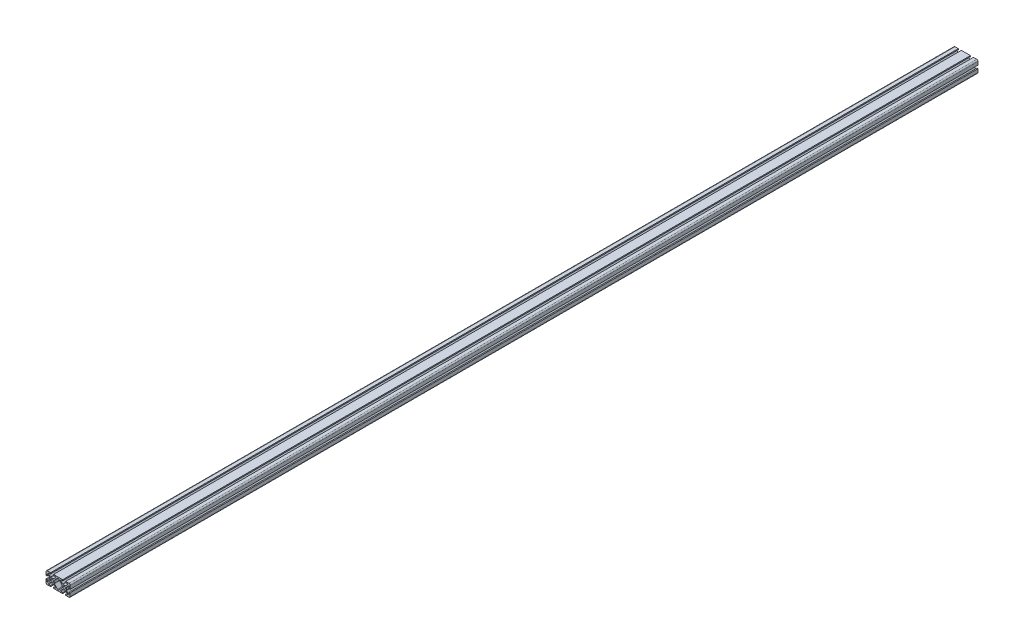
SolidWorks part; units mm, degrees
ref_plane "Front Plane" through (0, 0, 0) normal (0, 0, 1) x (1, 0, 0)
ref_plane "Top Plane" through (0, 0, 0) normal (0, 1, 0) x (1, 0, 0)
ref_plane "Right Plane" through (0, 0, 0) normal (1, 0, 0) x (0, 0, -1)
sketch "Sketch1" plane through (0, 0, 0) normal (0, 0, 1) x (1, 0, 0)
  line L0 (10, 10) -> (10, -10) construction
  line L1 (-20, 0) -> (20, 0) construction
  line L2 (12.5, -10) -> (20, -10)
  line L3 (20, -10) -> (20, -2.5)
  line L4 (12.5, -10) -> (12.5, -8.2134)
  line L5 (12.5, -8.2134) -> (16.95, -8.2134)
  line L6 (16.95, -8.2134) -> (12.3366, -3.6)
  line L7 (10, 0) -> (20, -10) construction
  line L8 (20, -2.5) -> (18.2134, -2.5)
  line L9 (18.2134, -2.5) -> (18.2134, -6.95)
  line L10 (18.2134, -6.95) -> (13.6, -2.3366)
  line L11 (15.9067, -4.6433) -> (14.6433, -5.9067) construction
  line L12 (0, 10) -> (0, -10) construction
  line L13 (0, -10) -> (-20, -10) construction
  line L14 (-10, 10) -> (10, 10) construction
  line L15 (20, 2.5) -> (20, -2.5) construction
  circle A0 centre (10, 0) radius 2.15
  arc A1 (15.5015, -8.2134) -> (15.9257, -7.1891) centre (15.5015, -7.6134) ccw construction
  point P8 (10, -3.6)
  point P16 (15.275, -5.275)
  point P30 (20, 0)
  dimension "Center Hole Diameter" = 4.3
  dimension "D3" = 0.6
  dimension "Rail Width" = 20
  dimension "T-Slot Width" = 5
  dimension "Slot Depth" = 6.4
  dimension "Rail Height" = 40
  dimension "Inner Slot Width" = 13.9
  dimension "Hole Spacing" = 20
sketch "Sketch2" plane through (0, 0, 0) normal (1, 0, 0) x (0, 0, -1)
  line L0 (-1524, -10) -> (1524, -10) construction
  line L1 (-1484, 0) -> (1484, 0) construction
  point P6 (-1484, 0)
  point P8 (1484, 0)
  dimension "Length" = 3048
  dimension "D1" = 40
sketch "Sketch3" plane through (0, 0, 0) normal (0, 0, 1) x (1, 0, 0)
  line L0 (12.5, -10) -> (17.9, -10)
  line L1 (12.5, -10) -> (20, -10) construction
  line L2 (12.5, -10) -> (12.5, -8.2134) construction
  line L3 (12.5, -8.2134) -> (16.95, -8.2134) construction
  line L4 (12.5, -8.2134) -> (12.5, -10)
  line L5 (12.5, -8.2134) -> (16.95, -8.2134)
  line L6 (10, -3.6) -> (12.3366, -3.6)
  line L7 (16.95, -8.2134) -> (12.3366, -3.6) construction
  line L8 (12.3366, -3.6) -> (16.95, -8.2134)
  line L9 (20, -10) -> (20, -2.5) construction
  line L10 (18.2134, -6.95) -> (13.6, -2.3366) construction
  line L11 (18.2134, -2.5) -> (18.2134, -6.95) construction
  line L12 (18.2134, -6.95) -> (18.2134, -2.5)
  line L13 (20, -2.5) -> (18.2134, -2.5) construction
  line L14 (18.2134, -2.5) -> (20, -2.5)
  line L15 (20, -2.5) -> (20, -7.9)
  line L16 (18.2134, -6.95) -> (13.6, -2.3366)
  line L17 (13.6, 0) -> (13.6, -2.3366)
  line L18 (-20, 0) -> (20, 0) construction
  line L19 (10, -3.6) -> (10, -2.15)
  line L20 (10, 10) -> (10, -10) construction
  line L21 (13.6, 0) -> (12.15, 0)
  arc A5 (17.9, -10) -> (20, -7.9) centre (17.9, -7.9) ccw
  circle A10 centre (10, 0) radius 2.15 construction
  arc A11 (10, -2.15) -> (12.15, 0) centre (10, 0) ccw
  dimension "D1" = 2.1
extrude "Boss-Extrude1" add sketch "Sketch3" along normal mid plane 3048
sketch "Sketch4" plane through (0, 0, 0) normal (0, 0, 1) x (1, 0, 0)
  line L0 (10, -3.6) -> (7.6634, -3.6)
  line L4 (7.6634, -3.6) -> (3.05, -8.2134)
  line L5 (3.05, -8.2134) -> (7.5, -8.2134)
  line L6 (7.5, -8.2134) -> (7.5, -10)
  line L18 (7.5, -10) -> (0, -10)
  line L19 (12.5, -10) -> (12.5, -8.2134) construction
  line L20 (12.5, -8.2134) -> (16.95, -8.2134) construction
  line L21 (10, -3.6) -> (12.3366, -3.6) construction
  line L22 (16.95, -8.2134) -> (12.3366, -3.6) construction
  line L23 (0, -8.7366) -> (6.4, -2.3366)
  line L24 (0, 10) -> (0, -10) construction
  line L25 (6.4, -2.3366) -> (6.4, 0)
  line L26 (-20, 0) -> (20, 0) construction
  line L27 (6.4, 0) -> (7.85, 0)
  line L28 (13.6, 0) -> (12.15, 0) construction
  line L29 (0, -8.7366) -> (0, -10)
  line L30 (10, -2.15) -> (10, -3.6)
  circle A4 centre (10, 0) radius 2.15 construction
  arc A5 (7.85, 0) -> (10, -2.15) centre (10, 0) ccw
extrude "Boss-Extrude2" add sketch "Sketch4" along normal mid plane 3048
mirror "Mirror1" about plane through (0, 0, 0) normal (1, 0, 0) of bodies 137 134
mirror "Mirror2" about plane through (0, 0, 0) normal (0, 1, 0) of bodies 135
fillet "Fillet1" radius 0.75 24 edges at (-7.6634, -3.6, 0) (-12.3366, -3.6, 0) (12.3366, -3.6, 0) (7.6634, -3.6, 0) (-3.05, -8.2134, 0) (-18.2134, -6.95, 0) (-16.95, -8.2134, 0) (-13.6, -2.3366, 0) (-18.2134, 6.95, 0) (-16.95, 8.2134, 0) (-12.3366, 3.6, 0) (-7.6634, 3.6, 0) (-13.6, 2.3366, 0) (-3.05, 8.2134, 0) (3.05, 8.2134, 0) (13.6, -2.3366, 0) (13.6, 2.3366, 0) (7.6634, 3.6, 0) (12.3366, 3.6, 0) (18.2134, 6.95, 0) (16.95, 8.2134, 0) (18.2134, -6.95, 0) (16.95, -8.2134, 0) (3.05, -8.2134, 0)
fillet "Fillet2" radius 1.25 6 edges at (0, -8.7366, 0) (-6.4, -2.3366, 0) (0, 8.7366, 0) (-6.4, 2.3366, 0) (6.4, -2.3366, 0) (6.4, 2.3366, 0)
sketch "Sketch5" plane through (-20, 0, 0) normal (-1, 0, 0) x (0, 0, 1)
  line L0 (1524, -10) -> (-1524, -10) construction
  line L1 (1524, 10) -> (-24, 10)
  line L2 (1524, 10) -> (1524, -10)
  line L3 (1524, -10) -> (-24, -10)
  line L4 (-24, 10) -> (-24, -10)
  dimension "D1" = 1500
extrude "Cut-Extrude1" cut sketch "Sketch5" against normal through all
equation "\"D1@Sketch3\" = \"D3@Sketch1\" * 3.5"
equation "\"D1@Boss-Extrude1\" = \"Length@Sketch2\""
equation "\"D1@Boss-Extrude2\" = \"Length@Sketch2\""
equation "\"D1@Sketch2\"=\"Rail Height@Sketch1\""
